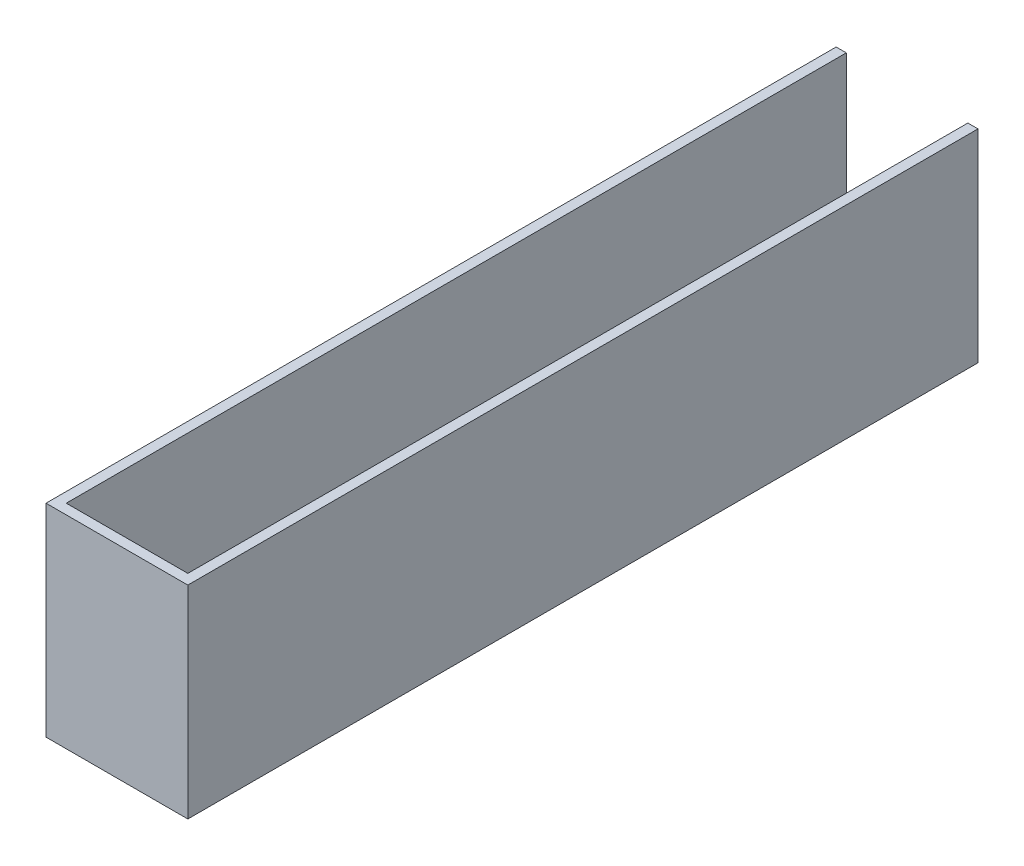
SolidWorks part; units mm, degrees
ref_plane "Front Plane" through (0, 0, 0) normal (0, 0, 1) x (1, 0, 0)
ref_plane "Top Plane" through (0, 0, 0) normal (0, 1, 0) x (1, 0, 0)
ref_plane "Right Plane" through (0, 0, 0) normal (1, 0, 0) x (0, 0, -1)
sketch "Sketch1" plane through (0, 0, 0) normal (0, 1, 0) x (1, 0, 0)
  line L0 (0, 0) -> (0, 780)
  line L1 (0, 780) -> (-10, 780)
  line L2 (-10, 780) -> (-10, 10)
  line L3 (-10, 10) -> (-130, 10)
  line L4 (-130, 10) -> (-130, 780)
  line L5 (-130, 780) -> (-140, 780)
  line L6 (-140, 780) -> (-140, 0)
  line L7 (-140, 0) -> (0, 0)
  dimension "D1" = 780
  dimension "D2" = 140
  dimension "D3" = 780
  dimension "D4" = 10
  dimension "D5" = 10
  dimension "D6" = 10
extrude "Boss-Extrude1" add sketch "Sketch1" along normal blind 200
